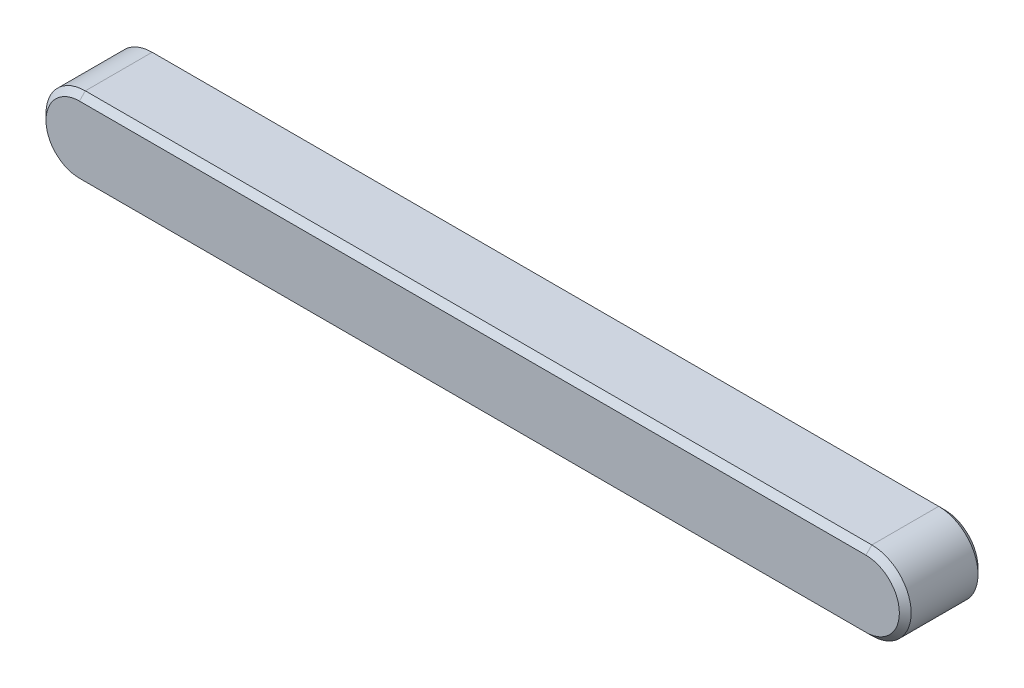
SolidWorks part; units mm, degrees
ref_plane "前视基准面" through (0, 0, 0) normal (0, 0, 1) x (1, 0, 0)
ref_plane "上视基准面" through (0, 0, 0) normal (0, 1, 0) x (1, 0, 0)
ref_plane "右视基准面" through (0, 0, 0) normal (1, 0, 0) x (0, 0, -1)
sketch "草图1" plane through (0, 0, 0) normal (0, 0, 1) x (1, 0, 0)
  line L0 (-20, 0) -> (20, 0) construction
  line L1 (-20, 2) -> (20, 2)
  line L2 (-20, -2) -> (20, -2)
  arc A0 (-20, 2) -> (-20, -2) centre (-20, 0) ccw
  arc A1 (20, -2) -> (20, 2) centre (20, 0) ccw
  point P2 (0, 0)
  dimension "D2" = 2
  dimension "D1" = 40
extrude "凸台-拉伸1" add sketch "草图1" along normal mid plane 4
chamfer "倒角1" distance 0.3 angle 45 8 edges at (22, 0, -2) (0, 2, -2) (0, -2, -2) (-22, 0, -2) (22, 0, 2) (0, 2, 2) (0, -2, 2) (-22, 0, 2)
